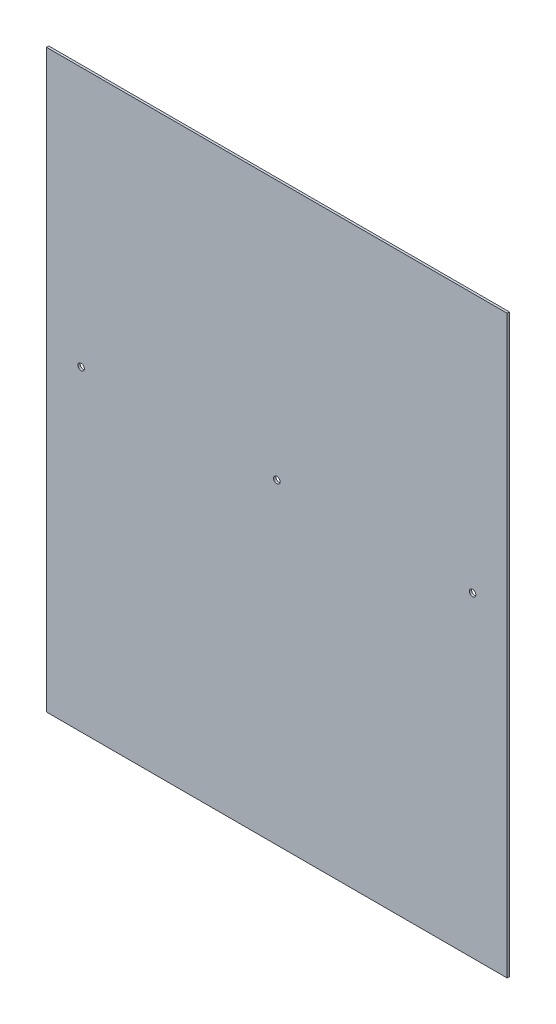
SolidWorks part; units mm, degrees
ref_plane "Front Plane" through (0, 0, 0) normal (0, 0, 1) x (1, 0, 0)
ref_plane "Top Plane" through (0, 0, 0) normal (0, 1, 0) x (1, 0, 0)
ref_plane "Right Plane" through (0, 0, 0) normal (1, 0, 0) x (0, 0, -1)
sketch "Sketch1" plane through (0, 0, 0) normal (0, 0, 1) x (1, 0, 0)
  line L1 (-200, 250) -> (200, 250)
  line L2 (-200, 250) -> (-200, -250)
  line L3 (-200, -250) -> (200, -250)
  line L4 (200, 250) -> (200, -250)
  line L5 (-200, 250) -> (200, -250) construction
  line L6 (-200, -250) -> (200, 250) construction
  point P0 (0, 0)
  dimension "D1" = 400
  dimension "D2" = 500
extrude "Boss-Extrude1" add sketch "Sketch1" along normal blind 2
extrude "Cut-Extrude2" cut sketch "Sketch3" along normal blind 60
sketch "Sketch3" plane through (0, 7.5418, 34) normal (0, 0, -1) x (-1, 0, 0)
  line L4 (200, 14.1784) -> (-200, 14.1784) construction
  line L5 (200, 19.8216) -> (-200, 19.8216) construction
  line L6 (-200, 476) -> (200, 476) construction
  line L7 (200, 484) -> (-200, 484) construction
  line L8 (0, 19.8216) -> (0, 14.1784) construction
  line L10 (-200, 248.5) -> (200, 248.5) construction
  line L11 (-170, 480) -> (170, 480) construction
  line L14 (0, 0) -> (0, 248.5) construction
  circle A0 centre (-170, 17) radius 2.8216
  circle A1 centre (0, 17) radius 2.8216
  circle A2 centre (170, 17) radius 2.8216
  circle A3 centre (170, 480) radius 2.8216
  circle A4 centre (0, 480) radius 2.8216
  circle A5 centre (-170, 480) radius 2.8216
